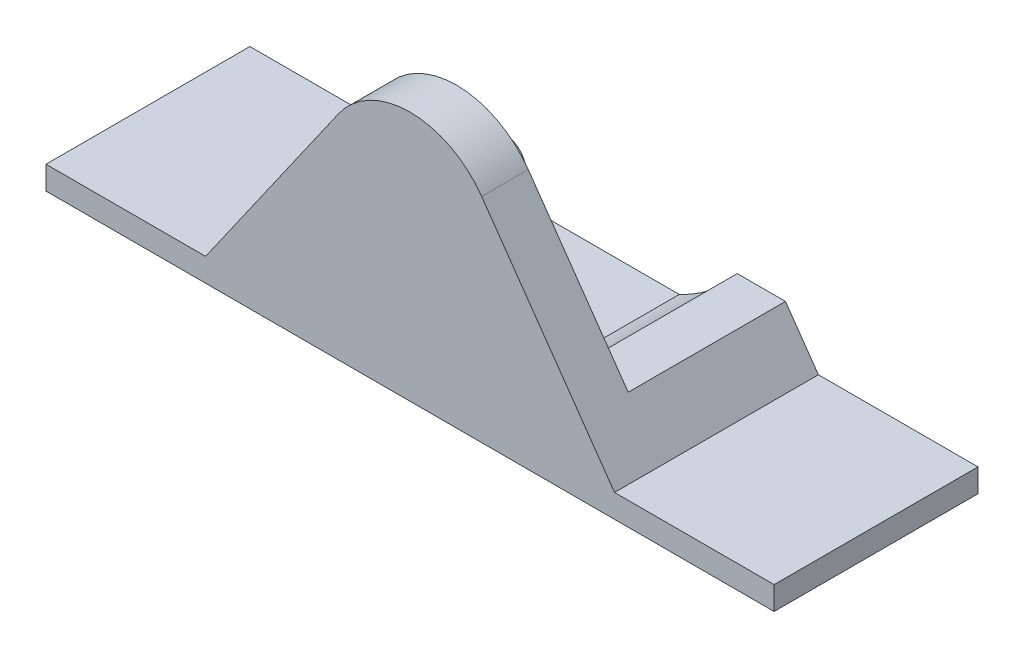
SolidWorks part; units mm, degrees
ref_plane "Front Plane" through (0, 0, 0) normal (0, 0, 1) x (1, 0, 0)
ref_plane "Top Plane" through (0, 0, 0) normal (0, 1, 0) x (1, 0, 0)
ref_plane "Right Plane" through (0, 0, 0) normal (1, 0, 0) x (0, 0, -1)
sketch "Sketch1" plane through (0, 0, 0) normal (0, 1, 0) x (1, 0, 0)
  line L1 (0, 0) -> (125, 0)
  line L2 (0, 0) -> (0, 35)
  line L3 (0, 35) -> (125, 35)
  line L4 (125, 0) -> (125, 35)
  dimension "D1" = 125
  dimension "D2" = 35
extrude "Boss-Extrude1" add sketch "Sketch1" along normal blind 4
sketch "Sketch3" plane through (0, 0, 0) normal (0, 0, 1) x (1, 0, 0)
  line L0 (62.5, 4) -> (62.5, 28) construction
  line L1 (0, 4) -> (125, 4) construction
  line L2 (50.2101, 36.5999) -> (27.3982, 4)
  line L3 (74.7899, 36.5999) -> (97.6018, 4)
  line L4 (27.3982, 4) -> (97.6018, 4)
  circle A0 centre (62.5, 28) radius 6 construction
  arc A1 (74.7899, 36.5999) -> (50.2101, 36.5999) centre (62.5, 28) ccw
  point P4 (97.6018, 4)
  dimension "D1" = 12
  dimension "D3" = 30
  dimension "D2" = 24
extrude "Boss-Extrude2" add sketch "Sketch3" against normal blind 8
sketch "Sketch4" plane through (0, 0, -8) normal (0, 0, -1) x (-1, 0, 0)
  arc A0 (-50.2101, 36.5999) -> (-74.7899, 36.5999) centre (-62.5, 28) ccw construction
  arc A1 (-50.2101, 36.5999) -> (-74.7899, 36.5999) centre (-62.5, 28) ccw construction
  circle A2 centre (-62.5, 28) radius 6
  dimension "D1" = 12
extrude "Boss-Extrude3" add sketch "Sketch4" along normal blind 1
sketch "Sketch5" plane through (0, 0, -9) normal (0, 0, -1) x (-1, 0, 0)
  circle A0 centre (-62.5, 28) radius 3.95
  circle A1 centre (-62.5, 28) radius 6 construction
  circle A2 centre (-62.5, 28) radius 6 construction
  point P5 (-62.5, 28.6178)
  dimension "D1" = 7.9
extrude "Boss-Extrude4" add sketch "Sketch5" along normal blind 7
sketch "Sketch8" plane through (0, 0, -8) normal (0, 0, -1) x (-1, 0, 0)
  line L0 (-51.2777, 4) -> (-27.3982, 4)
  line L1 (-91.9508, 12.0757) -> (-83.6745, 12.0757)
  line L2 (-50.2101, 36.5999) -> (-27.3982, 4) construction
  line L3 (-74.7899, 36.5999) -> (-97.6018, 4)
  line L4 (-97.6018, 4) -> (-27.3982, 4)
  line L5 (-27.3982, 4) -> (-50.2101, 36.5999)
  line L6 (-91.9508, 12.0757) -> (-97.6018, 4)
  line L7 (-97.6018, 4) -> (-73.7223, 4)
  line L8 (-27.3982, 4) -> (-33.0492, 12.0757)
  line L9 (-41.3255, 12.0757) -> (-33.0492, 12.0757)
  arc A0 (-83.6745, 12.0757) -> (-73.7223, 4) centre (-62.5, 28) ccw
  arc A1 (-50.2101, 36.5999) -> (-74.7899, 36.5999) centre (-62.5, 28) ccw
  arc A3 (-51.2777, 4) -> (-41.3255, 12.0757) centre (-62.5, 28) ccw
  point P5 (-83.6745, 12.0757)
  point P11 (-34.582, 14.2662)
  dimension "D1" = 0
extrude "Boss-Extrude5" add sketch "Sketch8" along normal up to surface (27 mm away) up to face at (62.5, 2, -35)
